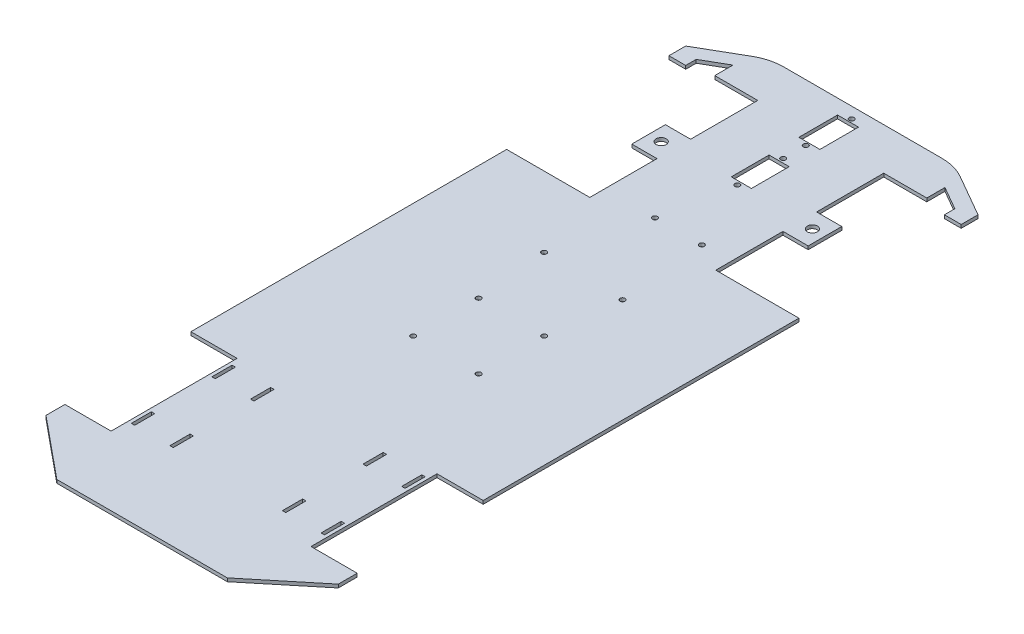
SolidWorks part; units mm, degrees
ref_plane "Front Plane" through (0, 0, 0) normal (0, 0, 1) x (1, 0, 0)
ref_plane "Top Plane" through (0, 0, 0) normal (0, 1, 0) x (1, 0, 0)
ref_plane "Right Plane" through (0, 0, 0) normal (1, 0, 0) x (0, 0, -1)
sketch "Sketch1" plane through (0, 0, 0) normal (0, 1, 0) x (1, 0, 0)
  line L0 (-132.8695, 0) -> (0, 0) construction
  line L1 (0, 113.4848) -> (0, -315.5584) construction
  line L2 (47.0265, 113.4848) -> (-47.0265, 113.4848)
  line L3 (-70, 60.3665) -> (-70, 14.2317) construction
  line L4 (-85.0262, 38.4848) -> (-28.9163, 38.4848) construction
  line L5 (-61.9962, 109.4831) -> (-87, 95.086)
  line L6 (-87, 95.086) -> (-87, 85.086)
  line L7 (-87, 85.086) -> (-77, 85.086)
  line L8 (-77, 85.086) -> (-77, 91.3133)
  line L9 (-37.5, 88.4848) -> (-37.5, 48.4848)
  line L10 (-37.5, 48.4848) -> (-52.5, 48.4848)
  line L11 (-52.5, 48.4848) -> (-52.5, 28.4848)
  line L12 (-52.5, 28.4848) -> (-37.5, 28.4848)
  line L13 (-37.5, 28.4848) -> (-37.5, -11.5152)
  line L14 (-37.5, -11.5152) -> (-87, -11.5152)
  line L15 (-87, -11.5152) -> (-87, -199.4845)
  line L17 (-87, -274.4845) -> (-59.5, -274.4845)
  line L18 (-45, -127.9152) -> (0, -127.9152) construction
  line L22 (-77, 91.3133) -> (-63.1055, 99.3137)
  line L23 (-63.1055, 99.3137) -> (-63.1055, 88.4848)
  line L24 (-63.1055, 88.4848) -> (-37.5, 88.4848)
  line L25 (-45, 38.4848) -> (-45, -234.4845) construction
  line L26 (-69.1239, -234.4845) -> (0, -234.4845) construction
  line L28 (-87, -199.4845) -> (-59.5, -199.4845)
  line L33 (-59.5, -199.4845) -> (-59.5, -274.4845)
  line L34 (-32.5, -264.4845) -> (-34.5, -264.4845)
  line L39 (-70, 14.2317) -> (-69.1239, -234.4845) construction
  line L48 (-34.5, -252.4845) -> (-34.5, -264.4845)
  line L53 (-32.5, -252.4845) -> (-34.5, -252.4845)
  line L54 (-32.5, -252.4845) -> (-32.5, -264.4845)
  line L94 (-87, -275.7422) -> (-87, -274.4845)
  line L96 (-50.7409, -315.5584) -> (50.7409, -315.5584)
  line L97 (-57.5, -252.4845) -> (-55.5, -252.4845)
  line L98 (-57.5, -252.4845) -> (-57.5, -264.4845)
  line L99 (-57.5, -264.4845) -> (-55.5, -264.4845)
  line L100 (-55.5, -252.4845) -> (-55.5, -264.4845)
  line L101 (-57.5, -252.4845) -> (-55.5, -264.4845) construction
  line L102 (-57.5, -264.4845) -> (-55.5, -252.4845) construction
  line L103 (-32.5, -216.4845) -> (-32.5, -204.4845)
  line L104 (-32.5, -216.4845) -> (-34.5, -216.4845)
  line L105 (-34.5, -216.4845) -> (-34.5, -204.4845)
  line L106 (-32.5, -204.4845) -> (-34.5, -204.4845)
  line L107 (-57.5, -204.4845) -> (-55.5, -204.4845)
  line L108 (-55.5, -216.4845) -> (-55.5, -204.4845)
  line L109 (-57.5, -216.4845) -> (-55.5, -216.4845)
  line L110 (-57.5, -216.4845) -> (-57.5, -204.4845)
  line L111 (57.5, -264.4845) -> (55.5, -252.4845) construction
  line L112 (57.5, -252.4845) -> (55.5, -264.4845) construction
  line L113 (70, 14.2317) -> (69.1239, -234.4845) construction
  line L114 (45, 38.4848) -> (45, -234.4845) construction
  line L115 (85.0262, 38.4848) -> (28.9163, 38.4848) construction
  line L116 (70, 60.3665) -> (70, 14.2317) construction
  line L117 (57.5, -216.4845) -> (57.5, -204.4845)
  line L118 (57.5, -216.4845) -> (55.5, -216.4845)
  line L119 (55.5, -216.4845) -> (55.5, -204.4845)
  line L120 (57.5, -204.4845) -> (55.5, -204.4845)
  line L121 (32.5, -204.4845) -> (34.5, -204.4845)
  line L122 (34.5, -216.4845) -> (34.5, -204.4845)
  line L123 (32.5, -216.4845) -> (34.5, -216.4845)
  line L124 (32.5, -216.4845) -> (32.5, -204.4845)
  line L125 (55.5, -252.4845) -> (55.5, -264.4845)
  line L126 (57.5, -264.4845) -> (55.5, -264.4845)
  line L127 (57.5, -252.4845) -> (57.5, -264.4845)
  line L128 (57.5, -252.4845) -> (55.5, -252.4845)
  line L130 (87, -275.7422) -> (87, -274.4845)
  line L131 (32.5, -252.4845) -> (32.5, -264.4845)
  line L132 (32.5, -252.4845) -> (34.5, -252.4845)
  line L133 (34.5, -252.4845) -> (34.5, -264.4845)
  line L134 (32.5, -264.4845) -> (34.5, -264.4845)
  line L135 (59.5, -199.4845) -> (59.5, -274.4845)
  line L136 (87, -199.4845) -> (59.5, -199.4845)
  line L137 (63.1055, 88.4848) -> (37.5, 88.4848)
  line L138 (63.1055, 99.3137) -> (63.1055, 88.4848)
  line L139 (77, 91.3133) -> (63.1055, 99.3137)
  line L140 (87, -274.4845) -> (59.5, -274.4845)
  line L141 (87, -11.5152) -> (87, -199.4845)
  line L142 (37.5, -11.5152) -> (87, -11.5152)
  line L143 (37.5, 28.4848) -> (37.5, -11.5152)
  line L144 (52.5, 28.4848) -> (37.5, 28.4848)
  line L145 (52.5, 48.4848) -> (52.5, 28.4848)
  line L146 (37.5, 48.4848) -> (52.5, 48.4848)
  line L147 (37.5, 88.4848) -> (37.5, 48.4848)
  line L148 (77, 85.086) -> (77, 91.3133)
  line L149 (87, 85.086) -> (77, 85.086)
  line L150 (87, 95.086) -> (87, 85.086)
  line L151 (61.9962, 109.4831) -> (87, 95.086)
  line L152 (-57.5, -216.4845) -> (-55.5, -204.4845) construction
  line L153 (-57.5, -204.4845) -> (-55.5, -216.4845) construction
  line L154 (-57.5, -210.4845) -> (-32.5, -210.4845) construction
  line L155 (-87, -275.7422) -> (-87, -285.7422)
  line L156 (-87, -285.7422) -> (-50.7409, -315.5584)
  line L157 (87, -275.7422) -> (87, -285.7422)
  line L158 (87, -285.7422) -> (50.7409, -315.5584)
  line L161 (6, 41.2048) -> (6, 63.7048)
  line L163 (-6, 41.2048) -> (-6, 63.7048)
  line L164 (6, 41.2048) -> (-6, 63.7048) construction
  line L165 (6, 63.7048) -> (-6, 41.2048) construction
  line L167 (6, 41.2048) -> (-6, 41.2048)
  line L168 (6, 63.7048) -> (-6, 63.7048)
  line L169 (-6, 52.4548) -> (6, 52.4548) construction
  line L170 (6.25, 93.2121) -> (-6.25, 93.2121) construction
  line L171 (6.25, 104.7121) -> (-6.25, 104.7121)
  line L172 (6.25, 104.7121) -> (6.25, 81.7121)
  line L173 (6.25, 81.7121) -> (-6.25, 81.7121)
  line L174 (-6.25, 104.7121) -> (-6.25, 81.7121)
  line L175 (6.25, 104.7121) -> (-6.25, 81.7121) construction
  line L176 (6.25, 81.7121) -> (-6.25, 104.7121) construction
  circle A0 centre (-45, 38.4848) radius 3
  arc A1 (-47.0265, 113.4848) -> (-61.9962, 109.4831) centre (-47.0265, 83.4848) ccw
  arc A2 (47.0265, 113.4848) -> (61.9962, 109.4831) centre (47.0265, 83.4848) cw
  circle A3 centre (45, 38.4848) radius 3
  circle A7 centre (0, 38.8048) radius 1.5
  circle A8 centre (0, 66.1048) radius 1.5
  circle A9 centre (0, 79.5621) radius 1.5
  circle A10 centre (0, 106.8621) radius 1.5
  point P32 (-52.5, 38.4848)
  point P39 (-45, 48.4848)
  point P41 (-45, -127.9152)
  point P44 (-56.5, -258.4845)
  point P104 (56.5, -258.4845)
  point P105 (45, -127.9152)
  point P108 (0, 52.4548)
  point P121 (0, 93.2121)
  dimension "D5" = 30
  dimension "D12" = 6
  dimension "D20" = 75
  dimension "D25" = 13.65
  dimension "D26" = 3
  dimension "D30" = 3
  dimension "D1" = 20
  dimension "D2" = 45
  dimension "D3" = 42
  dimension "D4" = 100
  dimension "D6" = 10
  dimension "D7" = 25
  dimension "D9" = 10.5
  dimension "D10" = 25
  dimension "D11" = 15
  dimension "D15" = 12
  dimension "D14" = 2
  dimension "D13" = 2
  dimension "D18" = 10
  dimension "D19" = 10
  dimension "D16" = 24
  dimension "D21" = 35
  dimension "D22" = 22.5
  dimension "D23" = 12
  dimension "D24" = 13.97
  dimension "D27" = 12.5
  dimension "D28" = 23
  dimension "D29" = 13.65
extrude "Boss-Extrude2" add sketch "Sketch1" along normal blind 2
hole_wizard "Ø3.0 (3) Diameter Hole1" positions "Sketch4" profile "Sketch5" hole size "Ø3.0" standard "ANSI Metric" end condition through all
sketch "Sketch4" plane through (-77.532, 2, -197.101) normal (0, 1, 0) x (1, 0, 0)
  point P0 (97.8638, -199.745)
  point P3 (69.9638, -199.745)
  point P6 (54.7638, -250.545)
  point P9 (102.5638, -251.645)
sketch "Sketch5" plane through (20.3318, 2, 2.644) normal (1, 0, 0) x (0, 0, 1)
  line L0 (0, 0) -> (0, 2)
  line L1 (0, 2) -> (1.5, 2)
  line L2 (1.5, 2) -> (1.5, 0)
  line L3 (1.5, 0) -> (0, 0)
  line L4 (0, -6.35) -> (0, 107.95) construction
  dimension "Thru Hole Dia." = 3
  dimension "Thru Hole Depth" = 2
hole_wizard "Ø3.0 (3) Diameter Hole2" positions "Sketch6" profile "Sketch7" hole size "Ø3.0" standard "ANSI Metric" end condition through all
sketch "Sketch6" plane through (-77.532, 4, -197.101) normal (0, 1, 0) x (1, 0, 0)
  point P0 (97.9188, -293.6731)
  point P1 (58.9188, -293.6731)
  point P2 (58.9188, -332.6731)
  point P3 (97.9188, -332.6731)
sketch "Sketch7" plane through (20.3868, 4, 96.5721) normal (1, 0, 0) x (0, 0, 1)
  line L0 (0, 0) -> (0, 4)
  line L1 (0, 4) -> (1.5, 4)
  line L2 (1.5, 4) -> (1.5, 0)
  line L3 (1.5, 0) -> (0, 0)
  line L4 (0, -6.35) -> (0, 107.95) construction
  dimension "Thru Hole Dia." = 3
  dimension "Thru Hole Depth" = 4
